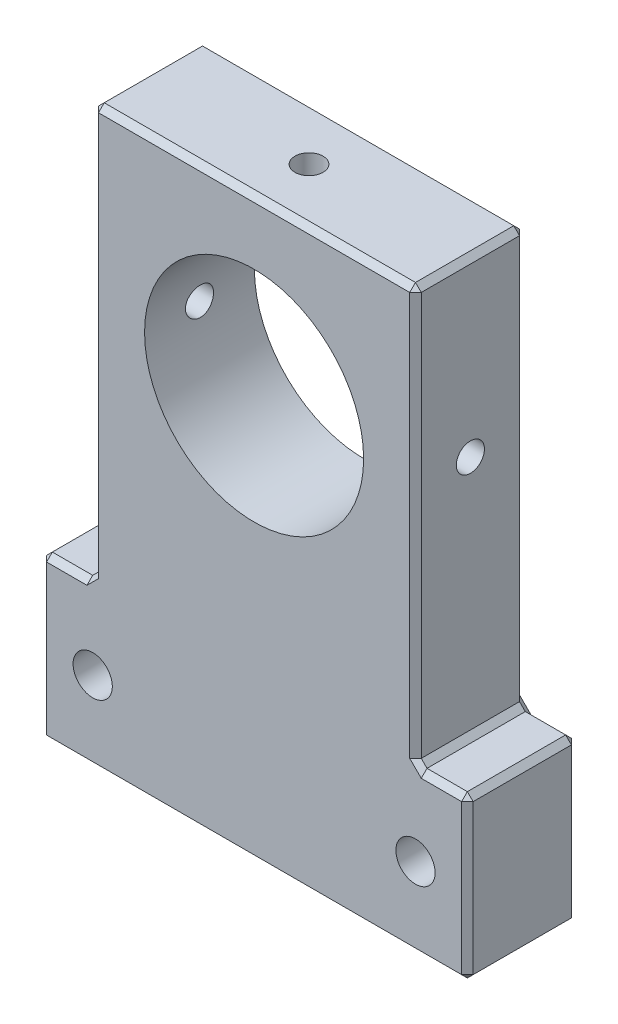
SolidWorks part; units mm, degrees
ref_plane "Front Plane" through (0, 0, 0) normal (0, 0, 1) x (1, 0, 0)
ref_plane "Top Plane" through (0, 0, 0) normal (0, 1, 0) x (1, 0, 0)
ref_plane "Right Plane" through (0, 0, 0) normal (1, 0, 0) x (0, 0, -1)
sketch "Sketch1" plane through (0, 0, 0) normal (0, 0, 1) x (-1, 0, 0)
  line L0 (-37, -50) -> (-37, 0)
  line L1 (-37, 0) -> (0, 0)
  line L2 (0, 0) -> (0, -50)
  line L3 (0, -50) -> (-37, -50)
  line L4 (-37, -50) -> (-36.8909, -50.0061)
  line L5 (-32.5, -50) -> (-32.5, -14)
  line L6 (-32.5, -14) -> (-37, -14)
  line L7 (0, -14) -> (-4.5, -14)
  line L8 (-4.5, -14) -> (-4.5, -50)
  circle A0 centre (-18.5, -35) radius 9.5
  circle A2 centre (-32.5, -7) radius 1.7
  circle A3 centre (-4.5, -7) radius 1.7
  dimension "D3" = 3.4
  dimension "D6" = 3.4
  dimension "D9" = 19
  dimension "D1" = 50
  dimension "D2" = 37
  dimension "D4" = 28
  dimension "D5" = 7
  dimension "D7" = 7
  dimension "D8" = 4.5
  dimension "D10" = 35
  dimension "D11" = 18.5
  dimension "D12" = 4.5
  dimension "D13" = 4.5
  dimension "D14" = 14
extrude "Boss-Extrude1" add sketch "Sketch1" along normal blind 9.525 contours L3 L2 L1 L0 A3 A2 A0
sketch "Sketch2" plane through (0, 0, 0) normal (0, 0, -1) x (-1, 0, 0)
  circle A0 centre (-32.5, 7) radius 3.25
  circle A1 centre (-4.5, 7) radius 3.25
  dimension "D1" = 6.5
  dimension "D2" = 6.5
extrude "Cut-Extrude1" cut sketch "Sketch2" against normal blind 5.5
sketch "Sketch3" plane through (4.5, 0, 0) normal (-1, 0, 0) x (0, 0, 1)
  line L0 (9.525, 0) -> (0, 0) construction
  line L1 (0, 14) -> (0, 50) construction
  circle A0 centre (4.7625, 35) radius 1.2195
  dimension "D3" = 2.439
  dimension "D1" = 35
  dimension "D2" = 4.7625
extrude "Cut-Extrude2" cut sketch "Sketch3" against normal through all
sketch "Sketch4" plane through (0, 50, 0) normal (0, 1, 0) x (1, 0, 0)
  line L0 (4.5, -9.525) -> (32.5, -9.525) construction
  line L1 (4.5, -9.525) -> (4.5, 0) construction
  circle A0 centre (18.5, -4.7625) radius 1.2195
  dimension "D3" = 2.439
  dimension "D1" = 4.7625
  dimension "D2" = 14
extrude "Cut-Extrude3" cut sketch "Sketch4" against normal up to surface (5.5 mm away)
chamfer "Chamfer1" distance 0.5 angle 45 26 edges at (18.5, 0, 9.525) (37, 0, 4.7625) (37, 7, 9.525) (34.75, 14, 9.525) (37, 14, 4.7625) (32.5, 32, 9.525) (32.5, 14, 4.7625) (32.5, 50, 4.7625) (18.5, 50, 9.525) (4.5, 50, 4.7625) (4.5, 32, 9.525) (2.25, 14, 9.525) (4.5, 14, 4.7625) (0, 7, 9.525) (0, 0, 4.7625) (0, 14, 4.7625) (0, 7, 0) (2.25, 14, 0) (4.5, 32, 0) (18.5, 50, 0) (32.5, 32, 0) (34.75, 14, 0) (37, 7, 0) (18.5, 0, 0) (29.25, 7, 0) (1.25, 7, 0)
